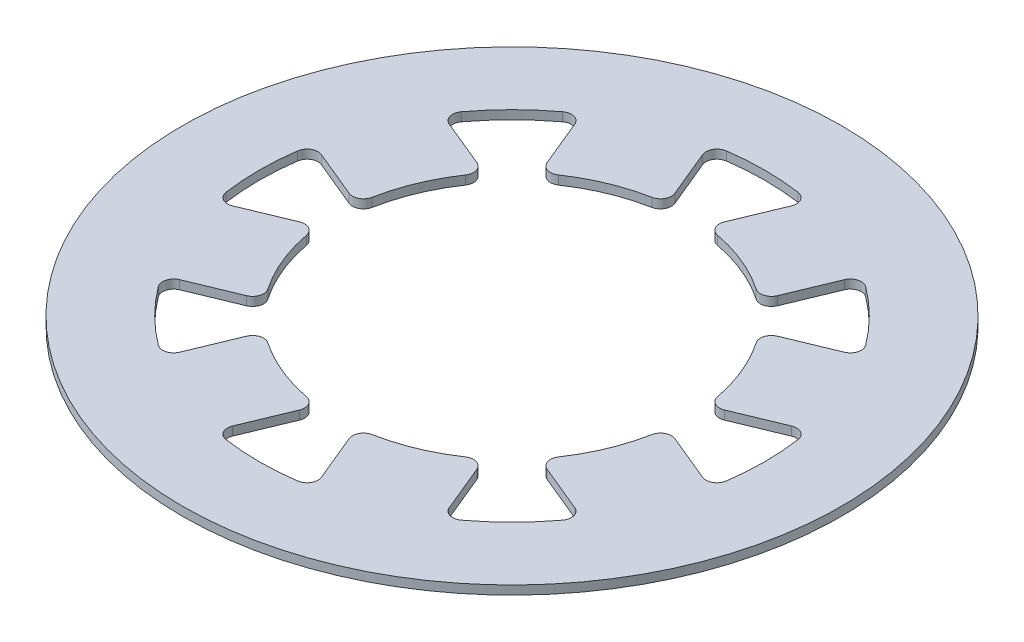
SolidWorks part; units mm, degrees
material "Plain Carbon Steel"
ref_plane "Front Plane" through (0, 0, 0) normal (0, 0, 1) x (1, 0, 0)
ref_plane "Top Plane" through (0, 0, 0) normal (0, 1, 0) x (1, 0, 0)
ref_plane "Right Plane" through (0, 0, 0) normal (1, 0, 0) x (0, 0, -1)
sketch "Sketch1" plane through (0, 0, 0) normal (0, 1, 0) x (1, 0, 0)
  line L0 (0, 0) -> (6.9291, 2.8701) construction
  line L1 (6.9291, -2.8701) -> (0, 0) construction
  line L2 (4.2706, -0.5642) -> (5.3488, -1.0108)
  line L3 (0, 0) -> (7.5, 0) construction
  line L4 (4.2706, 0.5642) -> (5.3488, 1.0108)
  line L5 (2.6209, -3.4187) -> (3.0674, -4.4969)
  line L6 (3.4187, -2.6209) -> (4.4969, -3.0674)
  line L7 (-0.5642, -4.2706) -> (-1.0108, -5.3488)
  line L8 (0.5642, -4.2706) -> (1.0108, -5.3488)
  line L9 (-3.4187, -2.6209) -> (-4.4969, -3.0674)
  line L10 (-2.6209, -3.4187) -> (-3.0674, -4.4969)
  line L11 (-4.2706, 0.5642) -> (-5.3488, 1.0108)
  line L12 (-4.2706, -0.5642) -> (-5.3488, -1.0108)
  line L13 (-2.6209, 3.4187) -> (-3.0674, 4.4969)
  line L14 (-3.4187, 2.6209) -> (-4.4969, 3.0674)
  line L15 (0.5642, 4.2706) -> (1.0108, 5.3488)
  line L16 (-0.5642, 4.2706) -> (-1.0108, 5.3488)
  line L17 (3.4187, 2.6209) -> (4.4969, 3.0674)
  line L18 (2.6209, 3.4187) -> (3.0674, 4.4969)
  circle A0 centre (0, 0) radius 7.5
  circle A1 centre (0, 0) radius 4 construction
  circle A2 centre (0, 0) radius 5.75 construction
  arc A3 (3.6955, -1.5307) -> (3.9294, -0.7484) centre (0, 0) ccw
  arc A4 (5.6919, -0.8152) -> (5.75, 0) centre (0, 0) ccw
  arc A5 (3.9294, 0.7484) -> (3.6955, 1.5307) centre (0, 0) ccw
  arc A6 (5.75, 0) -> (5.6919, 0.8152) centre (0, 0) ccw
  arc A7 (5.3488, -1.0108) -> (5.6919, -0.8152) centre (5.4444, -0.7798) ccw
  arc A8 (5.3488, 1.0108) -> (5.6919, 0.8152) centre (5.4444, 0.7798) cw
  arc A9 (3.9294, 0.7484) -> (4.2706, 0.5642) centre (4.175, 0.7951) ccw
  arc A10 (3.9294, -0.7484) -> (4.2706, -0.5642) centre (4.175, -0.7951) cw
  arc A11 (1.5307, -3.6955) -> (2.2493, -3.3077) centre (0, 0) ccw
  arc A12 (2.2493, -3.3077) -> (2.6209, -3.4187) centre (2.3899, -3.5144) cw
  arc A13 (3.0674, -4.4969) -> (3.4483, -4.6012) centre (3.2984, -4.4012) ccw
  arc A14 (3.4483, -4.6012) -> (4.0659, -4.0659) centre (0, 0) ccw
  arc A15 (4.0659, -4.0659) -> (4.6012, -3.4483) centre (0, 0) ccw
  arc A16 (4.4969, -3.0674) -> (4.6012, -3.4483) centre (4.4012, -3.2984) cw
  arc A17 (3.3077, -2.2493) -> (3.6955, -1.5307) centre (0, 0) ccw
  arc A18 (3.3077, -2.2493) -> (3.4187, -2.6209) centre (3.5144, -2.3899) ccw
  arc A19 (-1.5307, -3.6955) -> (-0.7484, -3.9294) centre (0, 0) ccw
  arc A20 (-0.7484, -3.9294) -> (-0.5642, -4.2706) centre (-0.7951, -4.175) cw
  arc A21 (-1.0108, -5.3488) -> (-0.8152, -5.6919) centre (-0.7798, -5.4444) ccw
  arc A22 (-0.8152, -5.6919) -> (0, -5.75) centre (0, 0) ccw
  arc A23 (0, -5.75) -> (0.8152, -5.6919) centre (0, 0) ccw
  arc A24 (1.0108, -5.3488) -> (0.8152, -5.6919) centre (0.7798, -5.4444) cw
  arc A25 (0.7484, -3.9294) -> (1.5307, -3.6955) centre (0, 0) ccw
  arc A26 (0.7484, -3.9294) -> (0.5642, -4.2706) centre (0.7951, -4.175) ccw
  arc A27 (-3.6955, -1.5307) -> (-3.3077, -2.2493) centre (0, 0) ccw
  arc A28 (-3.3077, -2.2493) -> (-3.4187, -2.6209) centre (-3.5144, -2.3899) cw
  arc A29 (-4.4969, -3.0674) -> (-4.6012, -3.4483) centre (-4.4012, -3.2984) ccw
  arc A30 (-4.6012, -3.4483) -> (-4.0659, -4.0659) centre (0, 0) ccw
  arc A31 (-4.0659, -4.0659) -> (-3.4483, -4.6012) centre (0, 0) ccw
  arc A32 (-3.0674, -4.4969) -> (-3.4483, -4.6012) centre (-3.2984, -4.4012) cw
  arc A33 (-2.2493, -3.3077) -> (-1.5307, -3.6955) centre (0, 0) ccw
  arc A34 (-2.2493, -3.3077) -> (-2.6209, -3.4187) centre (-2.3899, -3.5144) ccw
  arc A35 (-3.6955, 1.5307) -> (-3.9294, 0.7484) centre (0, 0) ccw
  arc A36 (-3.9294, 0.7484) -> (-4.2706, 0.5642) centre (-4.175, 0.7951) cw
  arc A37 (-5.3488, 1.0108) -> (-5.6919, 0.8152) centre (-5.4444, 0.7798) ccw
  arc A38 (-5.6919, 0.8152) -> (-5.75, 0) centre (0, 0) ccw
  arc A39 (-5.75, 0) -> (-5.6919, -0.8152) centre (0, 0) ccw
  arc A40 (-5.3488, -1.0108) -> (-5.6919, -0.8152) centre (-5.4444, -0.7798) cw
  arc A41 (-3.9294, -0.7484) -> (-3.6955, -1.5307) centre (0, 0) ccw
  arc A42 (-3.9294, -0.7484) -> (-4.2706, -0.5642) centre (-4.175, -0.7951) ccw
  arc A43 (-1.5307, 3.6955) -> (-2.2493, 3.3077) centre (0, 0) ccw
  arc A44 (-2.2493, 3.3077) -> (-2.6209, 3.4187) centre (-2.3899, 3.5144) cw
  arc A45 (-3.0674, 4.4969) -> (-3.4483, 4.6012) centre (-3.2984, 4.4012) ccw
  arc A46 (-3.4483, 4.6012) -> (-4.0659, 4.0659) centre (0, 0) ccw
  arc A47 (-4.0659, 4.0659) -> (-4.6012, 3.4483) centre (0, 0) ccw
  arc A48 (-4.4969, 3.0674) -> (-4.6012, 3.4483) centre (-4.4012, 3.2984) cw
  arc A49 (-3.3077, 2.2493) -> (-3.6955, 1.5307) centre (0, 0) ccw
  arc A50 (-3.3077, 2.2493) -> (-3.4187, 2.6209) centre (-3.5144, 2.3899) ccw
  arc A51 (1.5307, 3.6955) -> (0.7484, 3.9294) centre (0, 0) ccw
  arc A52 (0.7484, 3.9294) -> (0.5642, 4.2706) centre (0.7951, 4.175) cw
  arc A53 (1.0108, 5.3488) -> (0.8152, 5.6919) centre (0.7798, 5.4444) ccw
  arc A54 (0.8152, 5.6919) -> (0, 5.75) centre (0, 0) ccw
  arc A55 (0, 5.75) -> (-0.8152, 5.6919) centre (0, 0) ccw
  arc A56 (-1.0108, 5.3488) -> (-0.8152, 5.6919) centre (-0.7798, 5.4444) cw
  arc A57 (-0.7484, 3.9294) -> (-1.5307, 3.6955) centre (0, 0) ccw
  arc A58 (-0.7484, 3.9294) -> (-0.5642, 4.2706) centre (-0.7951, 4.175) ccw
  arc A59 (3.6955, 1.5307) -> (3.3077, 2.2493) centre (0, 0) ccw
  arc A60 (3.3077, 2.2493) -> (3.4187, 2.6209) centre (3.5144, 2.3899) cw
  arc A61 (4.4969, 3.0674) -> (4.6012, 3.4483) centre (4.4012, 3.2984) ccw
  arc A62 (4.6012, 3.4483) -> (4.0659, 4.0659) centre (0, 0) ccw
  arc A63 (4.0659, 4.0659) -> (3.4483, 4.6012) centre (0, 0) ccw
  arc A64 (3.0674, 4.4969) -> (3.4483, 4.6012) centre (3.2984, 4.4012) cw
  arc A65 (2.2493, 3.3077) -> (1.5307, 3.6955) centre (0, 0) ccw
  arc A66 (2.2493, 3.3077) -> (2.6209, 3.4187) centre (2.3899, 3.5144) ccw
  point P20 (5.6378, -1.1305)
  point P24 (5.6378, 1.1305)
  point P27 (3.9755, 0.4419)
  point P30 (3.9755, -0.4419)
  point P138 (0, 0)
  dimension "D1" = 15
  dimension "D2" = 8
  dimension "D3" = 1.75
  dimension "D5" = 0.25
  dimension "D4" = 45
  dimension "D6" = 8
extrude "Boss-Extrude1" add sketch "Sketch1" along normal blind 0.2 contours A0 A65 A66 L18 A64 A63 A62 A61 L17 A60 A59 A5 A9 L4 A8 A6 A4 A7 L2 A10 A3 A17 A18 L6 A16 A15 A14 A13 L5 A12 A11 A25 A26 L8 A24 A23 A22 A21 L7 A20 A19 A33 A34 L10 A32 A31 A30 A29 L9 A28
